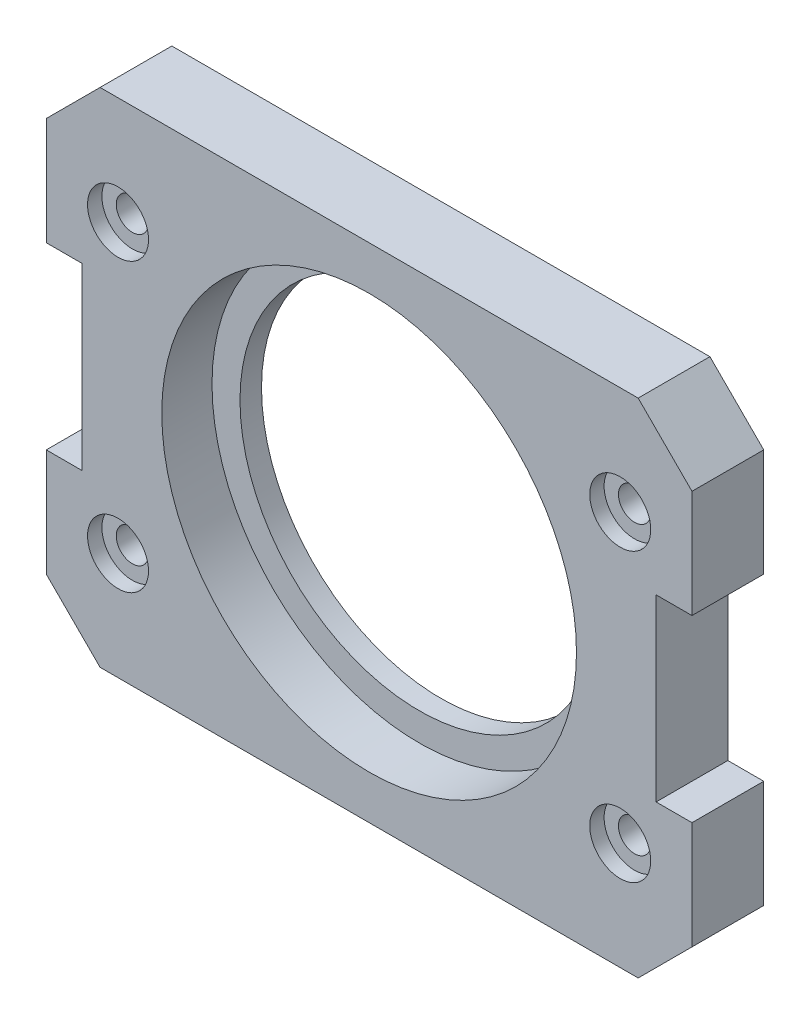
SolidWorks part; units mm, degrees
material "ABS"
ref_plane "Alzado" through (0, 0, 0) normal (0, 0, 1) x (1, 0, 0)
ref_plane "Planta" through (0, 0, 0) normal (0, 1, 0) x (1, 0, 0)
ref_plane "Vista lateral" through (0, 0, 0) normal (1, 0, 0) x (0, 0, -1)
sketch "Croquis1" plane through (0, 0, 0) normal (0, 0, 1) x (1, 0, 0)
  line L1 (-45, -35) -> (45, -35)
  line L2 (-45, -35) -> (-45, 35)
  line L3 (-45, 35) -> (45, 35)
  line L4 (45, -35) -> (45, 35)
  line L5 (-45, -35) -> (45, 35) construction
  line L6 (-45, 35) -> (45, -35) construction
  line L7 (-35, -20) -> (35, -20) construction
  line L8 (-35, -20) -> (-35, 20) construction
  line L9 (-35, 20) -> (35, 20) construction
  line L10 (35, -20) -> (35, 20) construction
  line L11 (-35, -20) -> (35, 20) construction
  line L12 (-35, 20) -> (35, -20) construction
  circle A0 centre (0, 0) radius 28.9
  circle A1 centre (35, 20) radius 2.25
  circle A2 centre (35, -20) radius 2.25
  circle A3 centre (-35, -20) radius 2.25
  circle A4 centre (-35, 20) radius 2.25
  point P0 (0, 0)
  dimension "D1" = 57.8
  dimension "D5" = 4.5
  dimension "D2" = 90
  dimension "D3" = 70
  dimension "D4" = 40
  dimension "D6" = 70
extrude "Saliente-Extruir1" add sketch "Croquis1" along normal mid plane 10
sketch "Croquis2" plane through (0, 0, -5) normal (0, 0, -1) x (-1, 0, 0)
  circle A0 centre (0, 0) radius 28.9 construction
  circle A1 centre (0, 0) radius 28.9
  circle A2 centre (0, 0) radius 25
  dimension "D1" = 50
extrude "Saliente-Extruir2" add sketch "Croquis2" against normal blind 3
sketch "Croquis3" plane through (0, 0, 5) normal (0, 0, 1) x (1, 0, 0)
  circle A0 centre (-35, 20) radius 4.25
  circle A1 centre (35, 20) radius 4.25
  circle A2 centre (35, -20) radius 4.25
  circle A3 centre (-35, -20) radius 4.25
  dimension "D1" = 8.5
extrude "Cortar-Extruir1" cut sketch "Croquis3" against normal blind 2
sketch "Croquis4" plane through (0, 0, 5) normal (0, 0, 1) x (1, 0, 0)
  line L0 (-45, 35) -> (-45, -35) construction
  line L1 (-50, -12.5) -> (-40, -12.5)
  line L2 (-50, -12.5) -> (-50, 12.5)
  line L3 (-50, 12.5) -> (-40, 12.5)
  line L4 (-40, -12.5) -> (-40, 12.5)
  line L5 (-50, -12.5) -> (-40, 12.5) construction
  line L6 (-50, 12.5) -> (-40, -12.5) construction
  line L7 (0, -5.5) -> (0, 5.5) construction
  line L8 (50, 12.5) -> (40, 12.5)
  line L9 (40, -12.5) -> (40, 12.5)
  line L10 (50, -12.5) -> (40, -12.5)
  line L11 (50, -12.5) -> (50, 12.5)
  point P0 (-45, 0)
  dimension "D1" = 25
  dimension "D2" = 10
extrude "Cortar-Extruir2" cut sketch "Croquis4" against normal through all
chamfer "Chaflán2" distance 7.5 angle 45 4 edges at (-45, -35, 0) (45, -35, 0) (45, 35, 0) (-45, 35, 0)
